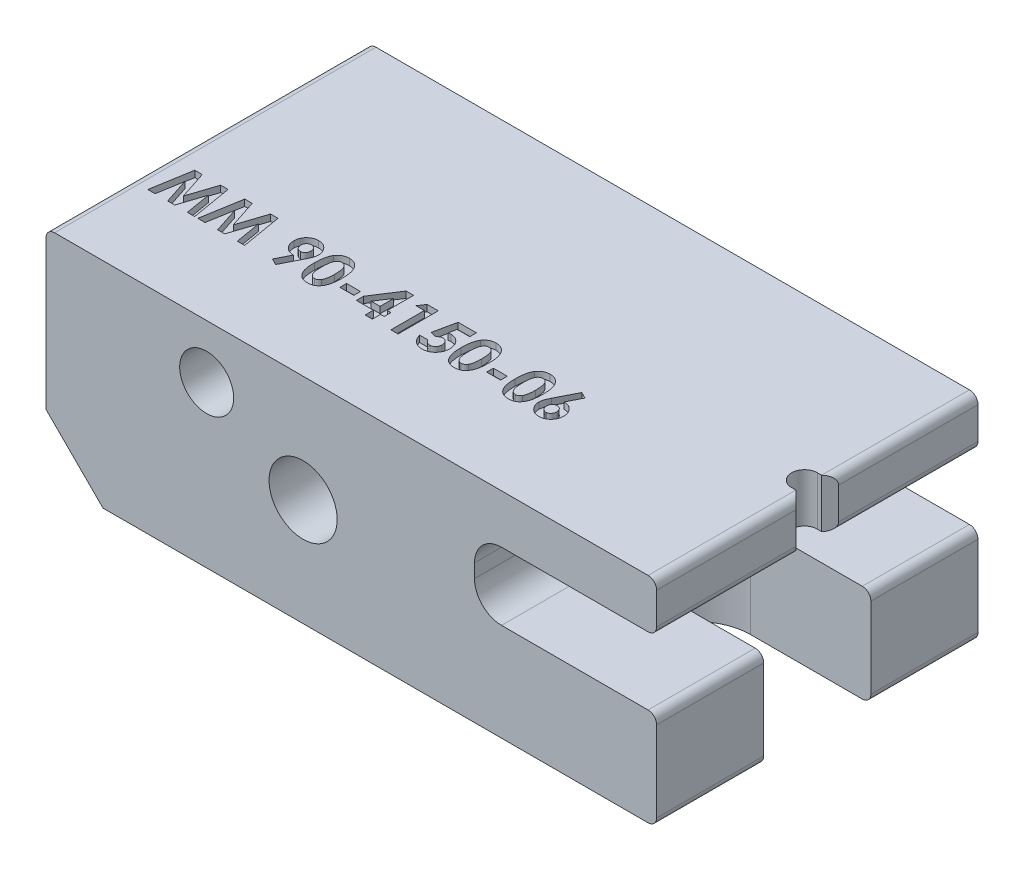
SolidWorks part; units mm, degrees
material "Acero M2"
ref_plane "Alzado" through (0, 0, 0) normal (0, 0, 1) x (1, 0, 0)
ref_plane "Planta" through (0, 0, 0) normal (0, 1, 0) x (1, 0, 0)
ref_plane "Vista lateral" through (0, 0, 0) normal (1, 0, 0) x (0, 0, -1)
sketch "Croquis1" plane through (0, 0, 0) normal (0, 1, 0) x (1, 0, 0)
  line L1 (0, 0) -> (36.195, 0)
  line L2 (0, 0) -> (0, -19.05)
  line L3 (0, -19.05) -> (36.195, -19.05)
  line L4 (36.195, 0) -> (36.195, -19.05)
  line L5 (18.0975, -19.05) -> (18.0975, 0) construction
  line L6 (0, -9.525) -> (36.195, -9.525) construction
  point P88 (18.0975, -9.525)
  dimension "D1" = 19.05
  dimension "D2" = 36.195
extrude "Saliente-Extruir1" add sketch "Croquis1" along normal blind 12.7
hole_wizard "Taladro roscado #10-321" positions "Croquis2" profile "Croquis3" tap size "#10-32" standard "Ansi Inch" end condition up to next
sketch "Croquis2" plane through (0, 0, 19.05) normal (0, 0, 1) x (1, 0, 0)
  line L0 (0, 12.7) -> (0, 0) construction
  line L1 (0, 12.7) -> (36.195, 12.7) construction
  point P0 (15.24, 6.35)
  dimension "D1" = 15.24
  dimension "D2" = 6.35
sketch "Croquis3" plane through (15.24, 6.35, 19.05) normal (1, 0, 0) x (0, -1, 0)
  line L0 (0, 0) -> (0, 19.05)
  line L1 (0, 19.05) -> (2.0193, 19.05)
  line L2 (2.0193, 19.05) -> (2.0193, 0)
  line L5 (2.0193, 0) -> (0, 0)
  line L11 (0, -6.35) -> (0, 107.95) construction
  dimension "Diámetro de perforador para roscar hasta el siguiente" = 4.0386
  dimension "Profundidad de perforador para roscar hasta el siguiente" = 19.05
cosmetic thread "Rosca de taladro1" parameters "D2"=4.826
hole_wizard "Taladros de espiga de 1/8 (0.126)1" positions "Croquis4" profile "Croquis5" hole size "1/8" standard "Ansi Inch" end condition through all
sketch "Croquis4" plane through (0, 0, 19.05) normal (0, 0, 1) x (1, 0, 0)
  line L0 (0, 12.7) -> (0, 0) construction
  line L1 (0, 12.7) -> (36.195, 12.7) construction
  point P0 (9.525, 9.525)
  dimension "D1" = 9.525
  dimension "D2" = 3.175
sketch "Croquis5" plane through (9.525, 9.525, 19.05) normal (1, 0, 0) x (0, -1, 0)
  line L0 (0, 0) -> (0, 19.05)
  line L1 (0, 19.05) -> (1.6002, 19.05)
  line L2 (1.6002, 19.05) -> (1.6002, 0)
  line L5 (1.6002, 0) -> (0, 0)
  line L11 (0, -6.35) -> (0, 107.95) construction
  dimension "Diámetro de taladro hasta el siguiente" = 3.2004
  dimension "Profundidad de taladro hasta el siguiente" = 19.05
sketch "Croquis6" plane through (0, 0, 19.05) normal (0, 0, 1) x (1, 0, 0)
  line L1 (36.195, 12.7) -> (36.195, 0) construction
  line L2 (36.195, 5.7912) -> (27.0002, 5.7912)
  line L3 (36.195, 9.8044) -> (27.0002, 9.8044)
  line L4 (0, 12.7) -> (36.195, 12.7) construction
  line L5 (25.4, 8.2042) -> (25.4, 7.3914)
  arc A0 (36.195, 5.7912) -> (36.195, 9.8044) centre (36.195, 7.7978) ccw
  arc A2 (27.0002, 9.8044) -> (25.4, 8.2042) centre (27.0002, 8.2042) ccw
  arc A3 (25.4, 7.3914) -> (27.0002, 5.7912) centre (27.0002, 7.3914) ccw
  dimension "D4" = 1.6002
  dimension "D1" = 4.0132
  dimension "D2" = 2.8956
  dimension "D3" = 10.795
extrude "Cortar-Extruir1" cut sketch "Croquis6" against normal through all
sketch "Croquis7" plane through (0, 0, 19.05) normal (0, 0, 1) x (1, 0, 0)
  line L0 (0, 3.3782) -> (3.3782, 0)
  line L1 (0, 12.7) -> (0, 0) construction
  line L2 (0, 0) -> (36.195, 0) construction
  line L3 (3.3782, 0) -> (0, 0)
  line L4 (0, 0) -> (0, 3.3782)
  line L5 (0, 12.7) -> (36.195, 12.7) construction
  dimension "D1" = 45
  dimension "D2" = 9.3218
extrude "Cortar-Extruir2" cut sketch "Croquis7" against normal through all
fillet "Redondeo1" radius 0.508 5 edges at (0, 12.7, 9.525) (36.195, 0, 9.525) (36.195, 5.7912, 9.525) (36.195, 9.8044, 9.525) (36.195, 12.7, 9.525)
sketch "Croquis8" plane through (0, 12.7, 0) normal (0, 1, 0) x (1, 0, 0)
  line L4 (36.195, -9.525) -> (35.433, -9.525) construction
  line L5 (36.195, 0) -> (36.195, -19.05) construction
  line L6 (36.195, -10.287) -> (35.433, -10.287)
  line L7 (36.195, -8.763) -> (35.433, -8.763)
  arc A3 (36.195, -10.287) -> (36.195, -8.763) centre (36.195, -9.525) ccw
  arc A4 (35.433, -8.763) -> (35.433, -10.287) centre (35.433, -9.525) ccw
  point P4 (35.814, -9.525)
  point P9 (34.671, -9.525)
  dimension "D1" = 1.524
  dimension "D2" = 0.762
extrude "Cortar-Extruir3" cut sketch "Croquis8" against normal through all
sketch "Croquis9" plane through (0, 0, 0) normal (0, 1, 0) x (1, 0, 0)
  line L0 (36.195, -9.525) -> (29.0576, -9.525) construction
  line L1 (36.195, -12.7) -> (29.0576, -12.7)
  line L2 (36.195, -6.35) -> (29.0576, -6.35)
  line L3 (36.195, 0) -> (36.195, -8.763) construction
  line L4 (35.687, 0) -> (0.508, 0) construction
  line L5 (36.195, 0) -> (36.195, -8.763) construction
  line L6 (29.0576, -9.525) -> (0.508, -9.525) construction
  line L7 (0.508, 0) -> (0.508, -19.05) construction
  arc A0 (36.195, -12.7) -> (36.195, -6.35) centre (36.195, -9.525) ccw
  arc A1 (29.0576, -6.35) -> (29.0576, -12.7) centre (29.0576, -9.525) ccw
  point P3 (32.6263, -9.525)
  point P8 (25.8826, -9.525)
  dimension "D1" = 10.3124
  dimension "D2" = 6.35
extrude "Cortar-Extruir4" cut sketch "Croquis9" along normal up to next
sketch "Croquis11" plane through (0, 12.7, 0) normal (0, 1, 0) x (1, 0, 0)
  line L0 (35.687, -8.763) -> (36.195, -8.255)
  line L1 (35.687, -8.763) -> (36.195, -8.763) construction
  line L2 (36.195, 0) -> (36.195, -8.763) construction
  line L3 (36.195, -8.255) -> (36.195, -8.763)
  line L4 (36.195, -8.763) -> (35.687, -8.763)
  line L5 (35.687, -10.287) -> (36.195, -10.795)
  line L6 (36.195, -10.287) -> (35.687, -10.287) construction
  line L7 (36.195, -10.287) -> (36.195, -19.05) construction
  line L8 (36.195, -10.795) -> (36.195, -10.287)
  line L9 (36.195, -10.287) -> (35.687, -10.287)
  dimension "D1" = 8.255
extrude "Cortar-Extruir5" cut sketch "Croquis11" against normal through all
sketch "Croquis12" plane through (0, 12.7, 0) normal (0, 1, 0) x (1, 0, 0)
  line L0 (0.9891, -14.0661) -> (35.2059, -14.0661) construction
  line L1 (18.0975, -14.0661) -> (18.0975, -19.05) construction
  line L2 (0.508, -19.05) -> (35.687, -19.05) construction
  text T0 "MM 90-4150-06" font "Century Gothic" height 2.3813
extrude "Cortar-Extruir6" cut sketch "Croquis12" against normal blind 0.381
